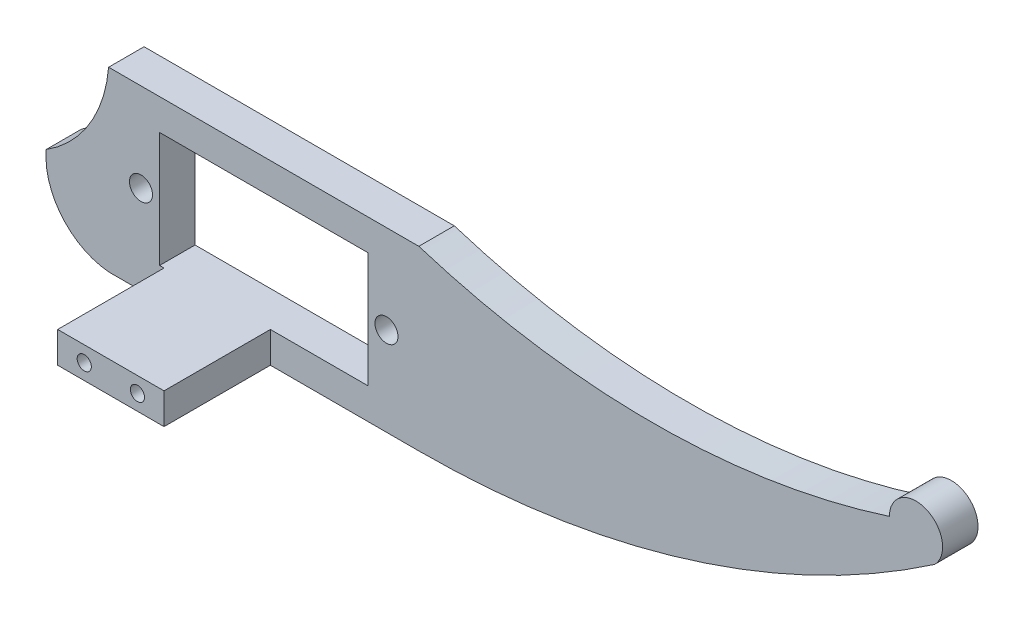
SolidWorks part; units mm, degrees
ref_plane "Front Plane" through (0, 0, 0) normal (0, 0, 1) x (1, 0, 0)
ref_plane "Top Plane" through (0, 0, 0) normal (0, 1, 0) x (1, 0, 0)
ref_plane "Right Plane" through (0, 0, 0) normal (1, 0, 0) x (0, 0, -1)
sketch "Sketch1" plane through (0, 0, 0) normal (0, 0, 1) x (1, 0, 0)
  line L1 (-4.3895, 3.8624) -> (19.1105, 3.8624)
  line L2 (-4.3895, 3.8624) -> (-4.3895, -9.1376)
  line L3 (-4.3895, -9.1376) -> (19.1105, -9.1376)
  line L4 (19.1105, 3.8624) -> (19.1105, -9.1376)
  line L5 (-10.1395, 7.3624) -> (24.8605, 7.3624)
  line L7 (-10.1395, -12.6376) -> (24.8605, -12.6376)
  arc A2 (-10.1395, 7.3624) -> (-17.1782, -4.1968) centre (-25.2144, 8.6193) cw
  arc A3 (-10.1395, -12.6376) -> (-17.1782, -4.1968) centre (-9.4384, -4.8979) cw
  arc A6 (82.1922, 4.7858) -> (77.9569, 7.5197) centre (80.9569, 7.5197) ccw
  arc A7 (24.8605, 7.3624) -> (77.9569, 7.5197) centre (51.1625, 90.5599) ccw
  arc A8 (24.8605, -12.6376) -> (83.036, 5.3569) centre (24.8605, 90.3991) ccw
  dimension "D1" = 23.5
  dimension "D2" = 13
  dimension "D3" = 3.5
  dimension "D4" = 3.5
extrude "Boss-Extrude1" add sketch "Sketch1" along normal blind 4 contours L7 A8 A6 A7 L5 A2 A3 L1 L4 L3 L2
sketch "Sketch4" plane through (0, 0, 4) normal (0, 0, -1) x (-1, 0, 0)
  line L0 (4.3895, -9.1376) -> (-19.1105, -9.1376) construction
  line L1 (-8.1105, -9.1376) -> (3.8895, -9.1376)
  line L2 (-8.1105, -9.1376) -> (-8.1105, -12.6376)
  line L3 (-8.1105, -12.6376) -> (3.8895, -12.6376)
  line L4 (3.8895, -9.1376) -> (3.8895, -12.6376)
  line L5 (-8.1105, -9.1376) -> (-8.1105, -12.6376) construction
  line L6 (10.1395, -12.6376) -> (-24.8605, -12.6376) construction
  line L7 (3.8895, -12.6376) -> (3.8895, -9.1376) construction
extrude "Boss-Extrude3" add sketch "Sketch4" against normal blind 12
sketch "Sketch6" plane through (0, 0, 4) normal (0, 0, 1) x (1, 0, 0)
  circle A0 centre (21.2105, -2.6376) radius 1.3
  circle A1 centre (-6.4895, -2.6376) radius 1.3
extrude "Cut-Extrude3" cut sketch "Sketch6" against normal blind 4
sketch "Sketch7" plane through (0, 0, 16) normal (0, 0, 1) x (1, 0, 0)
  circle A0 centre (5.1105, -10.8876) radius 0.8
  circle A1 centre (-0.8895, -10.8876) radius 0.8
extrude "Cut-Extrude4" cut sketch "Sketch7" against normal blind 3
